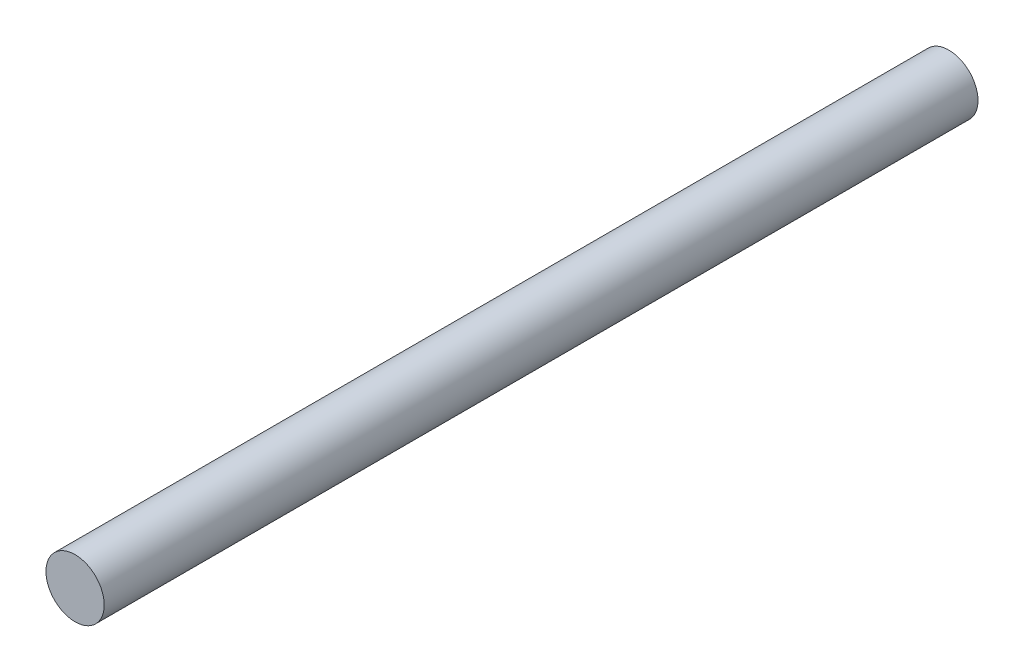
SolidWorks part; units mm, degrees
ref_plane "正面" through (0, 0, 0) normal (0, 0, 1) x (1, 0, 0)
ref_plane "平面" through (0, 0, 0) normal (0, 1, 0) x (1, 0, 0)
ref_plane "右側面" through (0, 0, 0) normal (1, 0, 0) x (0, 0, -1)
sketch "ｽｹｯﾁ1" plane through (0, 0, 0) normal (0, 0, 1) x (1, 0, 0)
  circle A0 centre (0, 0) radius 1
  dimension "D1" = 2
extrude "ﾎﾞｽ - 押し出し1" add sketch "ｽｹｯﾁ1" along normal blind 30
